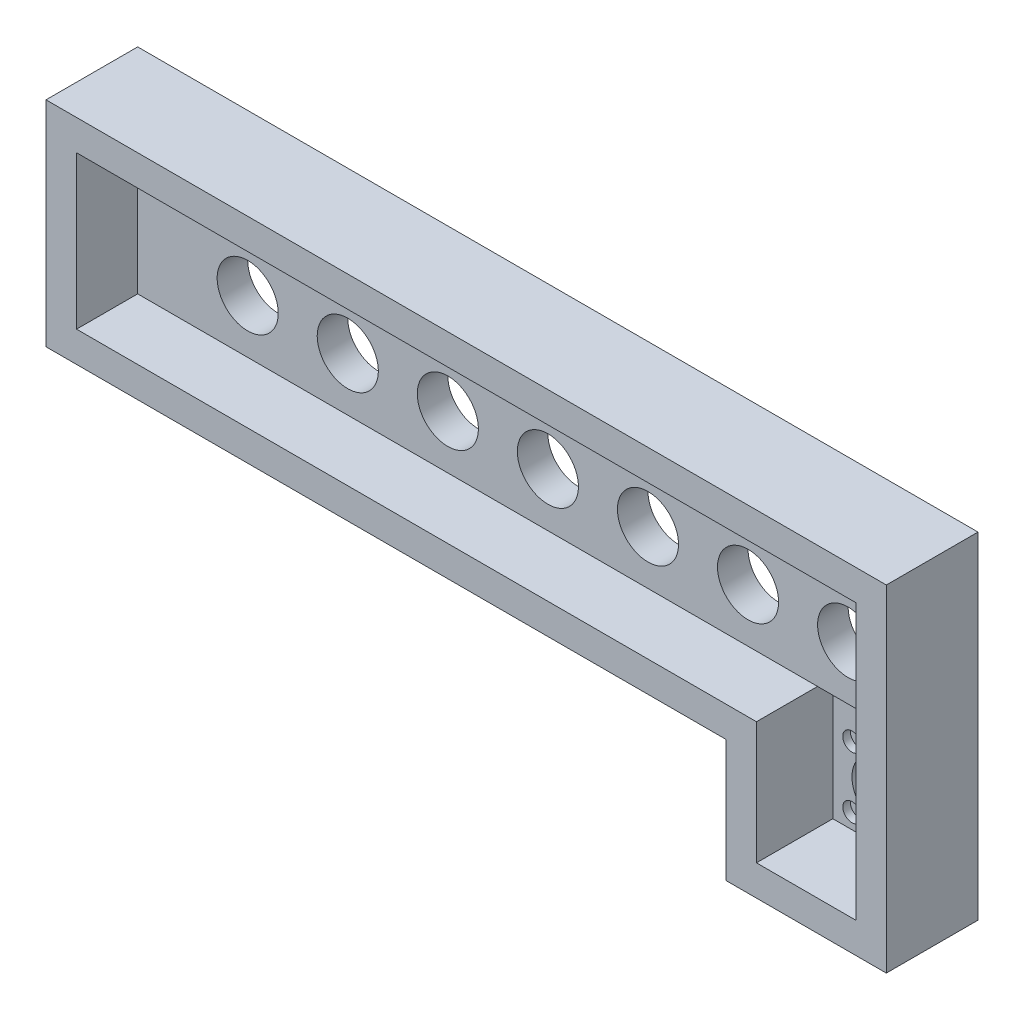
SolidWorks part; units mm, degrees
ref_plane "Front Plane" through (0, 0, 0) normal (0, 0, 1) x (1, 0, 0)
ref_plane "Top Plane" through (0, 0, 0) normal (0, 1, 0) x (1, 0, 0)
ref_plane "Right Plane" through (0, 0, 0) normal (1, 0, 0) x (0, 0, -1)
sketch "Sketch1" plane through (0, 0, 0) normal (0, 0, 1) x (1, 0, 0)
  line L6 (17, -7) -> (-27.5, -7)
  line L7 (-27.5, -7) -> (27.5, -7) construction
  line L8 (-27.5, -7) -> (-27.5, 7)
  line L9 (-27.5, 7) -> (27.5, 7)
  line L10 (27.5, -7) -> (27.5, 7)
  line L11 (0, 7) -> (0, -7) construction
  line L12 (-27.5, 0) -> (27.5, 0) construction
  line L13 (27.5, -7) -> (17, -7) construction
  line L14 (27.5, -7) -> (27.5, -15)
  line L15 (27.5, -15) -> (17, -15)
  line L16 (17, -7) -> (17, -15)
  point P0 (0, 0)
  dimension "D1" = 55
  dimension "D2" = 14
  dimension "D3" = 8
  dimension "D4" = 10.5
extrude "Boss-Extrude1" add sketch "Sketch1" along normal blind 6
shell "Shell1" thickness 2
sketch "Sketch3" plane through (0, 0, 0) normal (0, 0, -1) x (-1, 0, 0)
  line L0 (-27.5, -15) -> (-27.5, 7) construction
  line L1 (-23.5, 1) -> (-18.5, 1) construction
  line L2 (-23.5, 1) -> (-23.5, -4) construction
  line L3 (-23.5, -4) -> (-18.5, -4) construction
  line L4 (-18.5, 1) -> (-18.5, -4) construction
  line L5 (-21, -4) -> (-21, 1) construction
  line L6 (-23.5, -1.5) -> (-18.5, -1.5) construction
  line L8 (-16.95, 1) -> (-11.95, 1) construction
  line L9 (-11.95, 1) -> (-11.95, -4) construction
  line L10 (-16.95, -4) -> (-11.95, -4) construction
  line L11 (-16.95, 1) -> (-16.95, -4) construction
  line L12 (-10.4, 1) -> (-5.4, 1) construction
  line L13 (-5.4, 1) -> (-5.4, -4) construction
  line L14 (-10.4, -4) -> (-5.4, -4) construction
  line L15 (-10.4, 1) -> (-10.4, -4) construction
  line L16 (-3.85, 1) -> (1.15, 1) construction
  line L17 (1.15, 1) -> (1.15, -4) construction
  line L18 (-3.85, -4) -> (1.15, -4) construction
  line L19 (-3.85, 1) -> (-3.85, -4) construction
  line L20 (2.7, 1) -> (7.7, 1) construction
  line L21 (7.7, 1) -> (7.7, -4) construction
  line L22 (2.7, -4) -> (7.7, -4) construction
  line L23 (2.7, 1) -> (2.7, -4) construction
  line L24 (9.25, 1) -> (14.25, 1) construction
  line L25 (14.25, 1) -> (14.25, -4) construction
  line L26 (9.25, -4) -> (14.25, -4) construction
  line L27 (9.25, 1) -> (9.25, -4) construction
  line L28 (15.8, 1) -> (20.8, 1) construction
  line L29 (20.8, 1) -> (20.8, -4) construction
  line L30 (15.8, -4) -> (20.8, -4) construction
  line L31 (15.8, 1) -> (15.8, -4) construction
  line L32 (27.5, -7) -> (-17, -7) construction
  circle A0 centre (-21, -1.5) radius 2
  circle A1 centre (-14.45, -1.5) radius 2
  circle A2 centre (-7.9, -1.5) radius 2
  circle A3 centre (-1.35, -1.5) radius 2
  circle A4 centre (5.2, -1.5) radius 2
  circle A5 centre (11.75, -1.5) radius 2
  circle A6 centre (18.3, -1.5) radius 2
  dimension "D1" = 4
  dimension "D2" = 5
  dimension "D3" = 6.5
  dimension "D4" = 5.5
  dimension "D6" = 6.55
  dimension "D5" = 7
extrude "Cut-Extrude1" cut sketch "Sketch3" against normal through all
sketch "Sketch9" plane through (0, 0, 0) normal (0, 0, -1) x (-1, 0, 0)
  line L0 (-27.5, 7) -> (27.5, 7) construction
  line L1 (-27.5, -15) -> (-27.5, 7) construction
  circle A0 centre (-17.5, 2.8) radius 1.5
  circle A1 centre (8.5, 2.8) radius 1.5
  point P4 (0, 0)
  dimension "D1" = 3
  dimension "D2" = 4.2
  dimension "D3" = 10
  dimension "D4" = 26
extrude "Cut-Extrude6" cut sketch "Sketch9" against normal through all
sketch "Sketch11" plane through (0, 0, 2) normal (0, 0, 1) x (1, 0, 0)
  line L0 (19, -13) -> (25.5, -13) construction
  line L1 (19, -13) -> (25.5, -13) construction
  circle A0 centre (22.25, -10) radius 2
  point P4 (22.25, -13)
  dimension "D2" = 4
  dimension "D1" = 3
extrude "Cut-Extrude7" cut sketch "Sketch11" against normal through all
sketch "Sketch12" plane through (0, 0, 2) normal (0, 0, 1) x (1, 0, 0)
  line L1 (25.5, -13) -> (19, -13)
  line L2 (25.5, -13) -> (25.5, -5)
  line L3 (25.5, -5) -> (19, -5)
  line L4 (19, -13) -> (19, -5)
extrude "Cut-Extrude8" cut sketch "Sketch12" against normal blind 1
sketch "Sketch13" plane through (0, 0, 1) normal (0, 0, 1) x (1, 0, 0)
  line L1 (24.25, -12) -> (20.25, -12) construction
  line L2 (24.25, -12) -> (24.25, -8) construction
  line L3 (24.25, -8) -> (20.25, -8) construction
  line L4 (20.25, -12) -> (20.25, -8) construction
  line L5 (22.25, -8) -> (22.25, -12) construction
  line L6 (24.25, -10) -> (20.25, -10) construction
  circle A0 centre (20.25, -8) radius 0.6
  circle A1 centre (24.25, -8) radius 0.6
  circle A2 centre (24.25, -12) radius 0.6
  circle A3 centre (20.25, -12) radius 0.6
  point P0 (22.25, -10)
  dimension "D2" = 1.2
  dimension "D1" = 4
extrude "Cut-Extrude9" cut sketch "Sketch13" against normal blind 0.5
